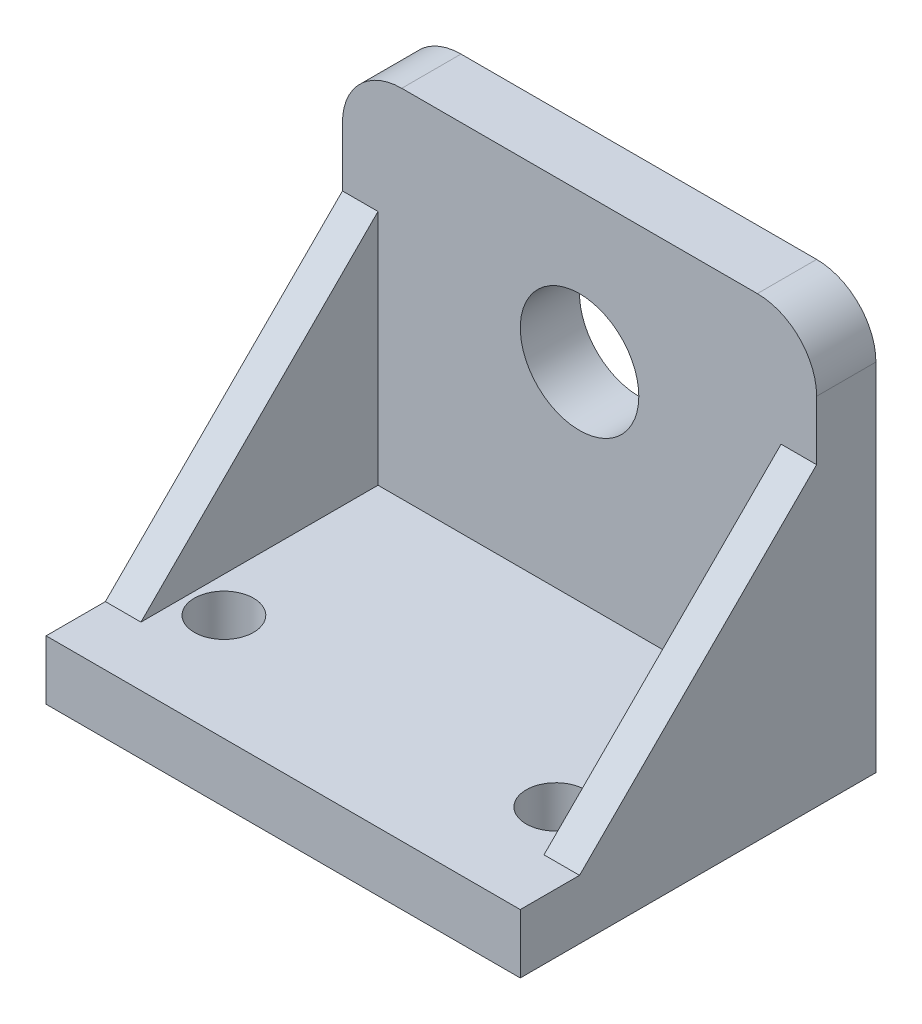
SolidWorks part; units mm, degrees
ref_plane "前视基准面" through (0, 0, 0) normal (0, 0, 1) x (1, 0, 0)
ref_plane "上视基准面" through (0, 0, 0) normal (0, 1, 0) x (1, 0, 0)
ref_plane "右视基准面" through (0, 0, 0) normal (1, 0, 0) x (0, 0, -1)
sketch "草图4" plane through (0, 0, 0) normal (0, 1, 0) x (1, 0, 0)
  line L0 (-40, 0) -> (40, 0)
  line L1 (40, 0) -> (40, -60)
  line L2 (40, -60) -> (-40, -60)
  line L3 (-40, -60) -> (-40, 0)
sketch "草图5" plane through (0, 0, 0) normal (0, 1, 0) x (1, 0, 0)
  line L0 (-40, 0) -> (40, 0)
  line L1 (40, 0) -> (40, -60)
  line L2 (40, -60) -> (-40, -60)
  line L3 (-40, -60) -> (-40, 0)
extrude "凸台-拉伸5" add sketch "草图5" along normal blind 10
sketch "草图6" plane through (0, 0, 0) normal (0, 0, 1) x (1, 0, 0)
  line L0 (-40, 0) -> (40, 0)
  line L1 (40, 0) -> (40, 60)
  line L2 (30, 70) -> (-30, 70)
  line L3 (-40, 60) -> (-40, 0)
  arc A0 (40, 60) -> (30, 70) centre (30, 60) ccw
  arc A1 (-30, 70) -> (-40, 60) centre (-30, 60) ccw
extrude "凸台-拉伸6" add sketch "草图6" along normal blind 10
ref_plane "基准面1" through (-40, 0, 0) normal (1, 0, 0) x (0, 0, -1)
ref_plane "基准面2" through (34, 0, 0) normal (1, 0, 0) x (0, 0, -1)
sketch "草图9" plane through (-40, 0, 0) normal (1, 0, 0) x (0, 0, -1)
  line L0 (-10, 10) -> (-50, 10)
  line L1 (-50, 10) -> (-10, 50)
  line L2 (-10, 50) -> (-10, 10)
extrude "凸台-拉伸9" add sketch "草图9" along normal blind 6
sketch "草图10" plane through (34, 0, 0) normal (1, 0, 0) x (0, 0, -1)
  line L0 (-10, 10) -> (-50, 10)
  line L1 (-50, 10) -> (-10, 50)
  line L2 (-10, 50) -> (-10, 10)
extrude "凸台-拉伸10" add sketch "草图10" along normal blind 6
sketch "草图11" plane through (0, 0, 0) normal (0, 0, 1) x (1, 0, 0)
  circle A0 centre (0, 45) radius 10
extrude "切除-拉伸1" cut sketch "草图11" along normal through all
sketch "草图13" plane through (0, 0, 0) normal (0, 1, 0) x (1, 0, 0)
  circle A0 centre (-28, -42) radius 5
  circle A1 centre (28, -42) radius 5
extrude "切除-拉伸3" cut sketch "草图13" along normal through all
